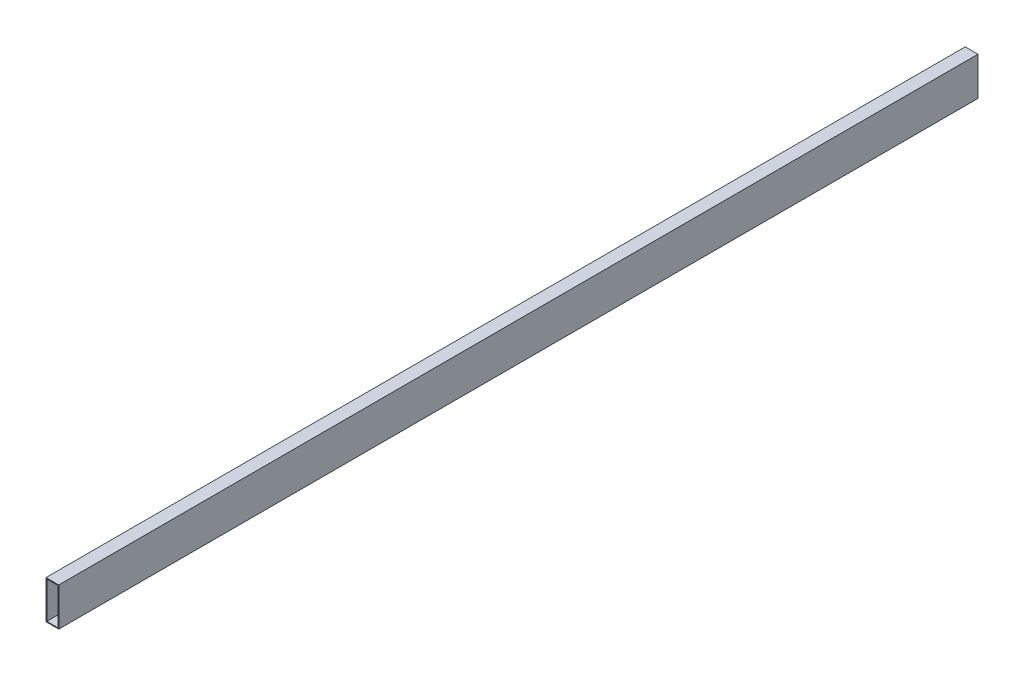
SolidWorks part; units mm, degrees
ref_plane "Front Plane" through (0, 0, 0) normal (0, 0, 1) x (1, 0, 0)
ref_plane "Top Plane" through (0, 0, 0) normal (0, 1, 0) x (1, 0, 0)
ref_plane "Right Plane" through (0, 0, 0) normal (1, 0, 0) x (0, 0, -1)
sketch "Sketch1" plane through (0, 0, 0) normal (0, 0, 1) x (1, 0, 0)
  line L1 (0, 0) -> (50.8, 0)
  line L2 (0, 0) -> (0, 152.4)
  line L3 (0, 152.4) -> (50.8, 152.4)
  line L4 (50.8, 0) -> (50.8, 152.4)
  dimension "D1" = 50.8
  dimension "D2" = 152.4
extrude "Boss-Extrude1" add sketch "Sketch1" along normal blind 3657.6
shell "Shell1" thickness 3.175
